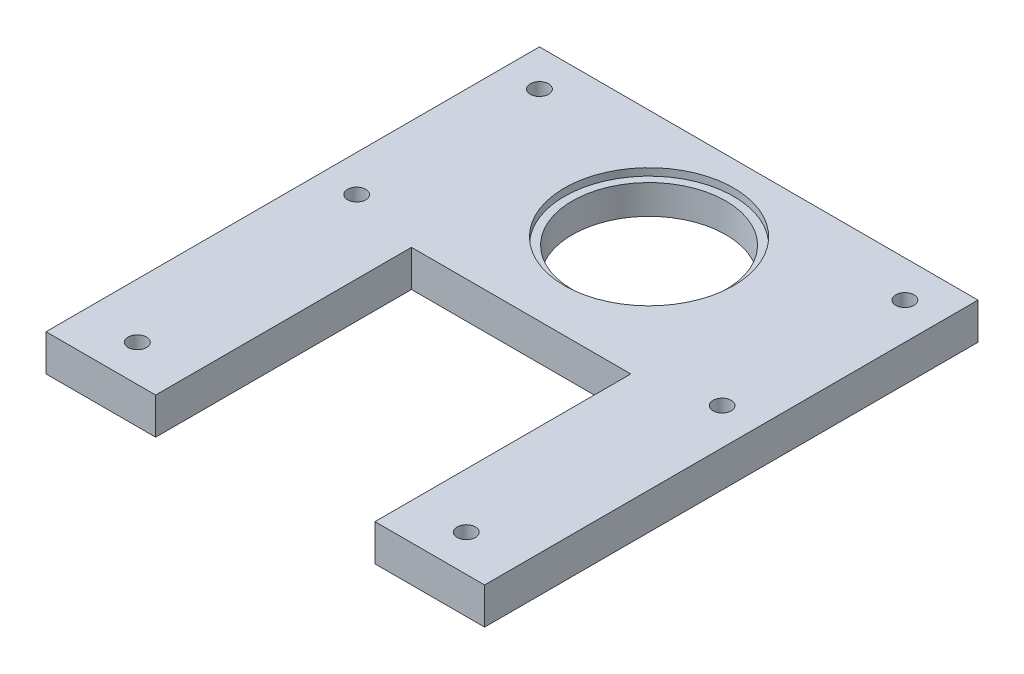
SolidWorks part; units mm, degrees
ref_plane "Front Plane" through (0, 0, 0) normal (0, 0, 1) x (1, 0, 0)
ref_plane "Top Plane" through (0, 0, 0) normal (0, 1, 0) x (1, 0, 0)
ref_plane "Right Plane" through (0, 0, 0) normal (1, 0, 0) x (0, 0, -1)
sketch "Sketch1" plane through (0, 0, 0) normal (0, 1, 0) x (1, 0, 0)
  line L1 (0, 0) -> (-152.4, 0)
  line L2 (0, 0) -> (0, 171.45)
  line L3 (0, 171.45) -> (-152.4, 171.45)
  line L4 (-152.4, 0) -> (-152.4, 171.45)
  dimension "D1" = 171.45
  dimension "D2" = 152.4
extrude "Boss-Extrude1" add sketch "Sketch1" along normal blind 12.7
sketch "Sketch2" plane through (0, 12.7, 0) normal (0, 1, 0) x (1, 0, 0)
  circle A0 centre (-76.2, 133.35) radius 26.67
  dimension "D1" = 53.34
extrude "Cut-Extrude1" cut sketch "Sketch2" against normal through all both and the other way through all
sketch "Sketch3" plane through (0, 12.7, 0) normal (0, 1, 0) x (1, 0, 0)
  circle A0 centre (-139.7, 158.75) radius 3.175
  circle A1 centre (-12.7, 158.75) radius 3.175
  circle A2 centre (-12.7, 95.25) radius 3.175
  circle A3 centre (-139.7, 95.25) radius 3.175
  dimension "D1" = 6.35
  dimension "D2" = 6.35
  dimension "D3" = 6.35
  dimension "D4" = 6.35
extrude "Cut-Extrude2" cut sketch "Sketch3" against normal through all both and the other way through all
sketch "Sketch4" plane through (0, 12.7, 0) normal (0, 1, 0) x (1, 0, 0)
  circle A0 centre (-76.2, 133.35) radius 29.4015
extrude "Cut-Extrude3" cut sketch "Sketch4" against normal blind 2.54
sketch "Sketch5" plane through (0, 0, 0) normal (0, -1, 0) x (1, 0, 0)
  line L0 (-152.4, 0) -> (0, 0) construction
  line L1 (-38.1, 0) -> (-114.3, 0)
  line L2 (-38.1, 0) -> (-38.1, -88.9)
  line L3 (-38.1, -88.9) -> (-114.3, -88.9)
  line L4 (-114.3, 0) -> (-114.3, -88.9)
  dimension "D1" = 88.9
  dimension "D2" = 76.2
extrude "Cut-Extrude4" cut sketch "Sketch5" against normal through all both and the other way through all
sketch "Sketch7" plane through (0, 0, 0) normal (0, -1, 0) x (1, 0, 0)
  circle A0 centre (-19.05, -12.7) radius 3.175
  circle A1 centre (-133.35, -12.7) radius 3.175
  dimension "D1" = 6.35
  dimension "D2" = 6.35
extrude "Cut-Extrude5" cut sketch "Sketch7" against normal through all both and the other way through all
